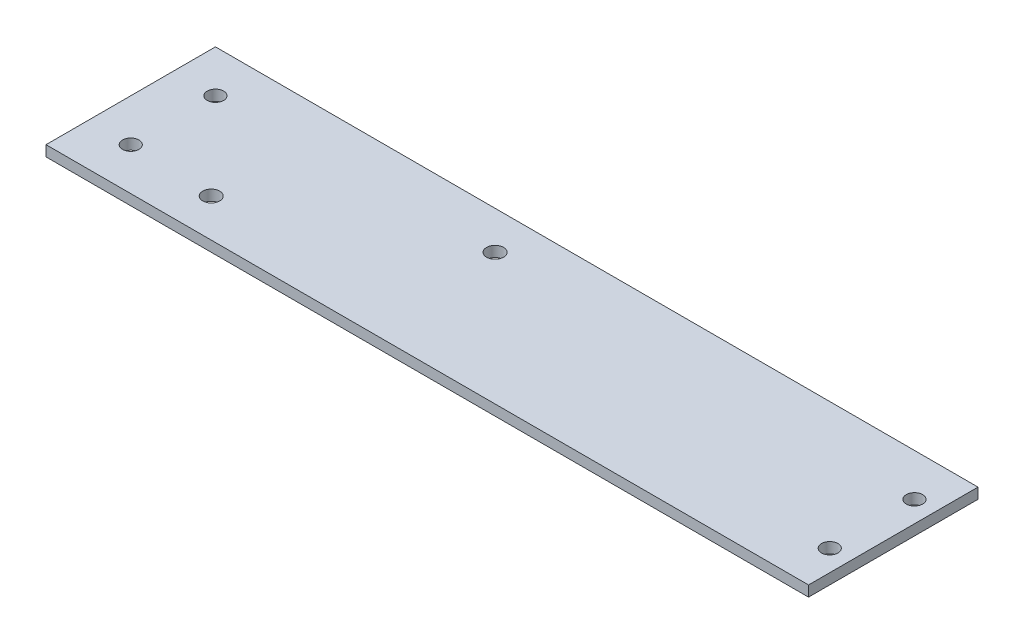
SolidWorks part; units mm, degrees
ref_plane "Front Plane" through (0, 0, 0) normal (0, 0, 1) x (1, 0, 0)
ref_plane "Top Plane" through (0, 0, 0) normal (0, 1, 0) x (1, 0, 0)
ref_plane "Right Plane" through (0, 0, 0) normal (1, 0, 0) x (0, 0, -1)
sketch "Sketch1" plane through (0, 0, 0) normal (0, 1, 0) x (1, 0, 0)
  line L1 (114.3, -25.4) -> (-114.3, -25.4)
  line L2 (114.3, -25.4) -> (114.3, 25.4)
  line L3 (114.3, 25.4) -> (-114.3, 25.4)
  line L4 (-114.3, -25.4) -> (-114.3, 25.4)
  line L5 (114.3, -25.4) -> (-114.3, 25.4) construction
  line L6 (114.3, 25.4) -> (-114.3, -25.4) construction
  point P0 (0, 0)
  dimension "D1" = 228.6
  dimension "D2" = 50.8
extrude "Boss-Extrude1" add sketch "Sketch1" along normal blind 3.175
hole_wizard "#10 (0.1935) Diameter Hole1" positions "Sketch2" profile "Sketch3" hole size "#10" standard "ANSI Inch" end condition through all
sketch "Sketch2" plane through (0, 3.175, 0) normal (0, 1, 0) x (1, 0, 0)
  line L0 (-101.6, 25.4) -> (-101.6, -25.4) construction
  line L1 (114.3, 25.4) -> (-114.3, 25.4) construction
  line L2 (-114.3, -25.4) -> (114.3, -25.4) construction
  line L4 (-114.3, 25.4) -> (-114.3, -25.4) construction
  line L5 (107.95, -25.4) -> (107.95, 25.4) construction
  line L7 (114.3, -25.4) -> (114.3, 25.4) construction
  point P11 (-101.6, -12.7)
  point P13 (-101.6, 12.7)
  point P23 (107.95, -12.7)
  point P25 (107.95, 12.7)
  dimension "D1" = 12.7
  dimension "D2" = 12.7
  dimension "D3" = 12.7
  dimension "D4" = 6.35
  dimension "D5" = 12.7
  dimension "D6" = 12.7
sketch "Sketch3" plane through (107.95, 3.175, -12.7) normal (1, 0, 0) x (0, 0, 1)
  line L0 (0, 0) -> (0, 3.175)
  line L1 (0, 3.175) -> (2.4574, 3.175)
  line L2 (2.4574, 3.175) -> (2.4574, 0)
  line L5 (2.4574, 0) -> (0, 0)
  line L11 (0, -6.35) -> (0, 107.95) construction
  dimension "Thru Hole Dia." = 4.9149
  dimension "Thru Hole Depth" = 3.175
hole_wizard "1/4-20 Tapped Hole1" positions "Sketch4" profile "Sketch5" tap size "1/4-20" standard "ANSI Inch" end condition through all
sketch "Sketch4" plane through (0, 3.175, 0) normal (0, 1, 0) x (1, 0, 0)
  line L0 (-114.3, 25.4) -> (-88.9, 25.4) construction
  line L1 (114.3, 25.4) -> (-114.3, 25.4) construction
  line L3 (-88.9, 25.4) -> (-88.9, -25.4) construction
  line L4 (-114.3, -25.4) -> (114.3, -25.4) construction
  line L6 (-88.9, 0) -> (-76.2, 0) construction
  line L7 (-76.2, -13.97) -> (-76.2, 0) construction
  line L9 (-76.2, 0) -> (-19.05, 0) construction
  line L10 (-19.05, 0) -> (-19.05, 13.97) construction
  point P42 (-19.05, 13.97)
  point P47 (-76.2, -13.97)
  dimension "D1" = 25.4
  dimension "D2" = 57.15
  dimension "D3" = 12.7
sketch "Sketch5" plane through (-76.2, 3.175, 13.97) normal (1, 0, 0) x (0, 0, 1)
  line L0 (0, 0) -> (0, 3.175)
  line L1 (0, 3.175) -> (2.5527, 3.175)
  line L2 (2.5527, 3.175) -> (2.5527, 0)
  line L5 (2.5527, 0) -> (0, 0)
  line L11 (0, -6.35) -> (0, 107.95) construction
  dimension "Thread Major Dia." = 5.1054
  dimension "Thru Tap Drill Depth" = 3.175
